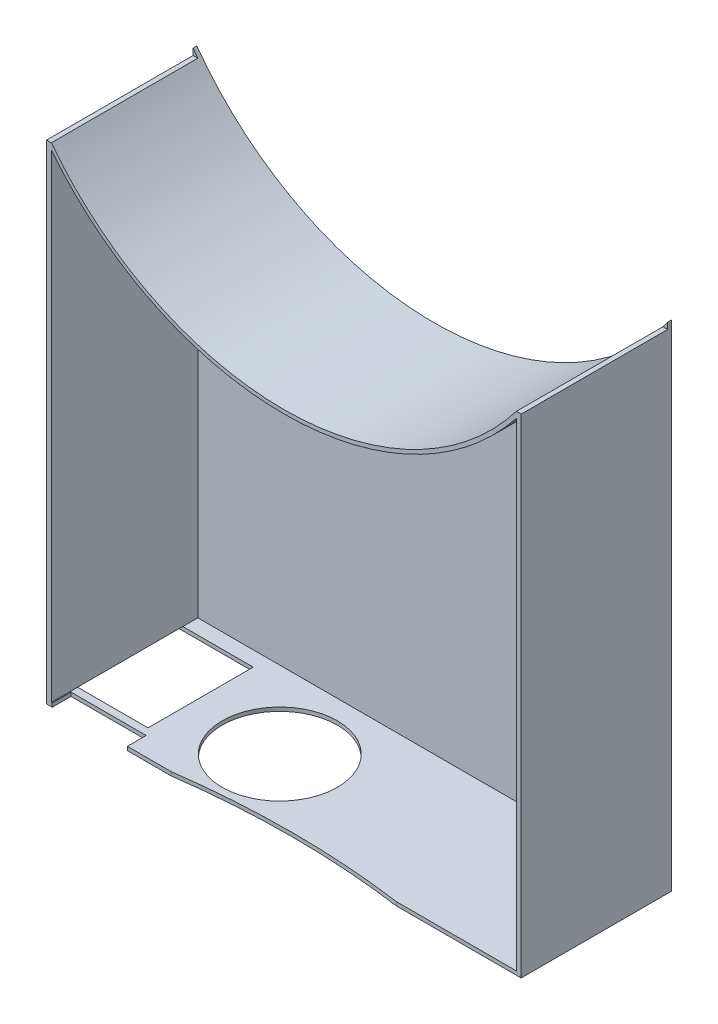
SolidWorks part; units mm, degrees
ref_plane "Front Plane" through (0, 0, 0) normal (0, 0, 1) x (1, 0, 0)
ref_plane "Top Plane" through (0, 0, 0) normal (0, 1, 0) x (1, 0, 0)
ref_plane "Right Plane" through (0, 0, 0) normal (1, 0, 0) x (0, 0, -1)
sketch "Sketch1" plane through (0, 0, 0) normal (0, 0, 1) x (1, 0, 0)
  line L0 (-61.9028, -47.4557) -> (61.9028, -47.4557)
  line L1 (61.9028, -47.4557) -> (63.1582, -47.4557)
  line L2 (-61.9028, -47.4557) -> (-63.1582, -47.4557)
  circle A0 centre (0, 0) radius 78
  circle A1 centre (0, 0) radius 79
  arc A2 (-63.1582, -47.4557) -> (63.1582, -47.4557) centre (0, 0) ccw
  arc A3 (-61.9028, -47.4557) -> (61.9028, -47.4557) centre (0, 0) ccw
  dimension "D1" = 156
  dimension "D2" = 158
ref_plane "Plane1" through (0, 0, 0) normal (0, 0, 1) x (1, 0, 0)
sketch "Sketch2" plane through (0, 0, 0) normal (0, 0, 1) x (1, 0, 0)
  line L0 (61.9028, -47.4557) -> (63.1582, -47.4557)
  line L1 (-63.1582, -47.4557) -> (-61.9028, -47.4557)
  arc A0 (-61.9028, -47.4557) -> (61.9028, -47.4557) centre (0, 0) ccw
  arc A1 (-63.1582, -47.4557) -> (63.1582, -47.4557) centre (0, 0) ccw
extrude "Boss-Extrude1" add sketch "Sketch2" against normal blind 40
sketch "Sketch3" plane through (0, -47.4557, 0) normal (0, 1, 0) x (1, 0, 0)
  line L0 (-63.1582, 0) -> (63.1582, 0) construction
  line L1 (-63.1582, 0) -> (-61.9028, 0)
  line L2 (-63.1582, 0) -> (-63.1582, 40)
  line L3 (-63.1582, 40) -> (-61.9028, 40)
  line L4 (-61.9028, 0) -> (-61.9028, 40)
  line L5 (-61.9028, 0) -> (-63.1582, 0) construction
  line L6 (63.1582, 40) -> (63.1582, 0) construction
  line L7 (61.9028, 40) -> (63.1582, 40)
  line L8 (61.9028, 40) -> (61.9028, 0)
  line L9 (61.9028, 0) -> (63.1582, 0)
  line L10 (63.1582, 40) -> (63.1582, 0)
extrude "Boss-Extrude2" add sketch "Sketch3" against normal blind 130
sketch "Sketch4" plane through (0, -177.4557, 0) normal (0, -1, 0) x (1, 0, 0)
  line L0 (63.1582, 0) -> (63.1582, -40) construction
  line L1 (-63.1582, -40) -> (63.1582, -40)
  line L2 (-63.1582, -40) -> (-63.1582, -39)
  line L3 (-63.1582, -39) -> (63.1582, -39)
  line L4 (63.1582, -40) -> (63.1582, -39)
  dimension "D1" = 1
extrude "Boss-Extrude3" add sketch "Sketch4" against normal blind 150
sketch "Sketch5" plane through (0, 0, -39) normal (0, 0, 1) x (1, 0, 0)
  circle A0 centre (0, 0) radius 78
extrude "Cut-Extrude3" cut sketch "Sketch5" against normal blind 90
sketch "Sketch6" plane through (0, 0, -39) normal (0, 0, 1) x (1, 0, 0)
  line L0 (63.1582, -177.4557) -> (63.1582, -47.4557) construction
  line L1 (-63.1582, -177.4557) -> (63.1582, -177.4557)
  line L2 (-63.1582, -177.4557) -> (-63.1582, -176.4557)
  line L3 (-63.1582, -176.4557) -> (63.1582, -176.4557)
  line L4 (63.1582, -177.4557) -> (63.1582, -176.4557)
  dimension "D1" = 1
extrude "Boss-Extrude4" add sketch "Sketch6" along normal blind 39
sketch "Sketch7" plane through (0, -177.4557, 0) normal (0, -1, 0) x (1, 0, 0)
  line L0 (0, 0) -> (-30, 0)
  line L1 (-63.1582, 0) -> (63.1582, 0) construction
  line L2 (0, 0) -> (30, 0)
  arc A0 (-30, 0) -> (30, 0) centre (0, 215.7674) ccw
  dimension "D1" = 30
  dimension "D2" = 30
extrude "Cut-Extrude4" cut sketch "Sketch7" against normal blind 39
sketch "Sketch8" plane through (0, -177.4557, 0) normal (0, -1, 0) x (1, 0, 0)
  line L0 (79, 0) -> (-79, 0) construction
  line L1 (-61.6582, 0) -> (-41.6582, 0)
  line L2 (-61.6582, 0) -> (-61.6582, -5)
  line L3 (-61.6582, -5) -> (-41.6582, -5)
  line L4 (-41.6582, 0) -> (-41.6582, -5)
  line L5 (-63.1582, -40) -> (-63.1582, 0) construction
  line L7 (-63.1582, -7) -> (-43.1582, -7)
  line L8 (-63.1582, -7) -> (-63.1582, -35)
  line L9 (-63.1582, -35) -> (-43.1582, -35)
  line L10 (-43.1582, -7) -> (-43.1582, -35)
  dimension "D1" = 1.5
  dimension "D2" = 20
  dimension "D3" = 5
  dimension "D4" = 28
  dimension "D5" = 2
  dimension "D6" = 20
extrude "Cut-Extrude5" cut sketch "Sketch8" against normal blind 1 and the other way through all
sketch "Sketch9" plane through (0, -177.4557, 0) normal (0, -1, 0) x (1, 0, 0)
  circle A0 centre (-19.5877, -18.4993) radius 15.3356
extrude "Cut-Extrude6" cut sketch "Sketch9" against normal blind 1
